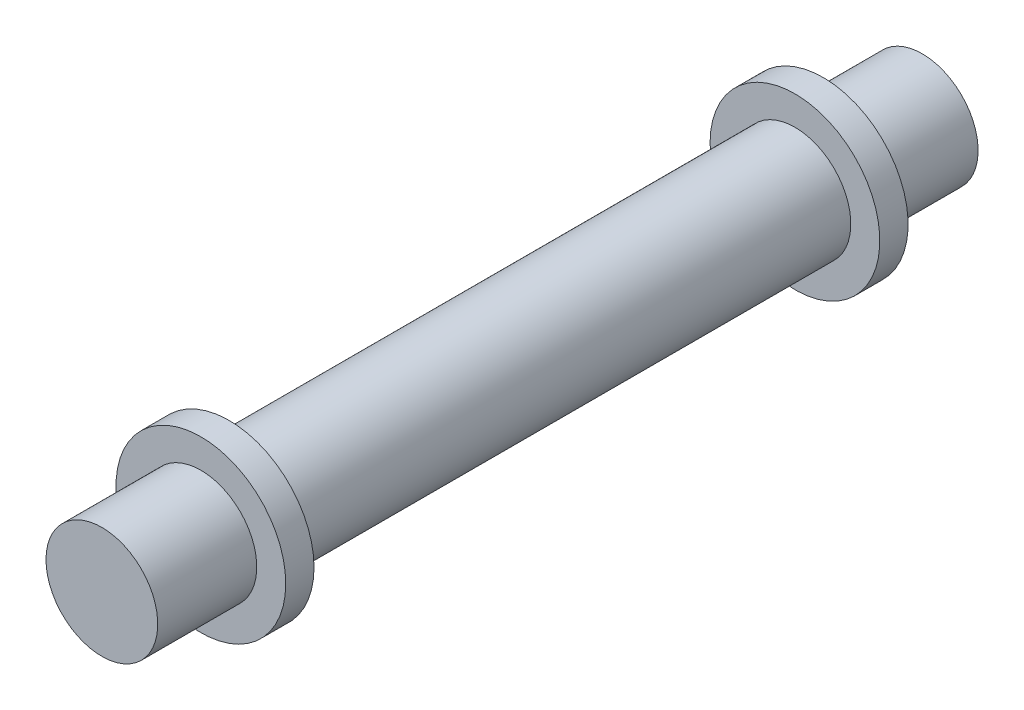
SolidWorks part; units mm, degrees
ref_plane "Ön Düzlem" through (0, 0, 0) normal (0, 0, 1) x (1, 0, 0)
ref_plane "Üst Düzlem" through (0, 0, 0) normal (0, 1, 0) x (1, 0, 0)
ref_plane "Sağ Düzlem" through (0, 0, 0) normal (1, 0, 0) x (0, 0, -1)
sketch "Sketch1" plane through (0, 0, 0) normal (0, 0, 1) x (1, 0, 0)
  circle A0 centre (0, 0) radius 3.95
  dimension "D1" = 7.9
extrude "Boss-Extrude1" add sketch "Sketch1" along normal blind 58
ref_plane "Plane1" through (0, 0, 51) normal (0, 0, 1) x (1, 0, 0)
sketch "Sketch2" plane through (0, 0, 51) normal (0, 0, 1) x (1, 0, 0)
  circle A0 centre (0, 0) radius 6
  dimension "D1" = 12
extrude "Boss-Extrude2" add sketch "Sketch2" against normal blind 2
ref_plane "Plane2" through (0, 0, 7) normal (0, 0, -1) x (-1, 0, 0)
sketch "Sketch3" plane through (0, 0, 7) normal (0, 0, -1) x (-1, 0, 0)
  circle A0 centre (0, 0) radius 6
  dimension "D1" = 12
extrude "Boss-Extrude3" add sketch "Sketch3" against normal blind 2
